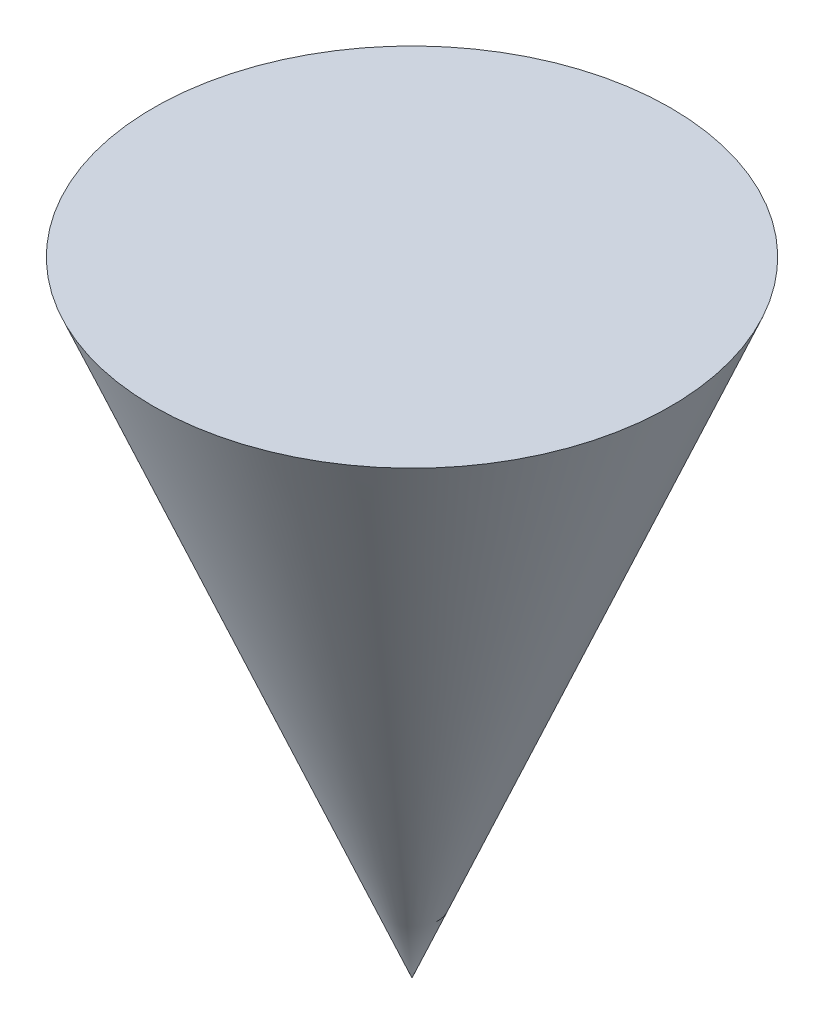
SolidWorks part; units mm, degrees
ref_plane "Front Plane" through (0, 0, 0) normal (0, 0, 1) x (1, 0, 0)
ref_plane "Top Plane" through (0, 0, 0) normal (0, 1, 0) x (1, 0, 0)
ref_plane "Right Plane" through (0, 0, 0) normal (1, 0, 0) x (0, 0, -1)
sketch "Sketch1" plane through (0, 0, 0) normal (0, 0, 1) x (1, 0, 0)
  line L0 (0, 0) -> (0, 48.8658) construction
  line L1 (0, 0) -> (8.2843, 20)
  line L2 (8.2843, 20) -> (0, 20)
  line L3 (0, 20) -> (0, 0)
  dimension "D1" = 20
  dimension "D2" = 22.5
revolve "Revolve1" add sketch "Sketch1" angle 360 about L0
